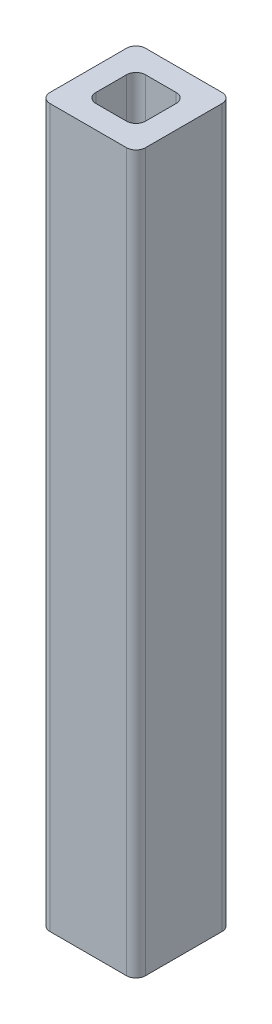
SolidWorks part; units mm, degrees
ref_plane "正面" through (0, 0, 0) normal (0, 0, 1) x (1, 0, 0)
ref_plane "平面" through (0, 0, 0) normal (0, 1, 0) x (1, 0, 0)
ref_plane "右側面" through (0, 0, 0) normal (1, 0, 0) x (0, 0, -1)
sketch "ｽｹｯﾁ1" plane through (0, 0, 0) normal (0, 1, 0) x (1, 0, 0)
  line L1 (-4, -5) -> (4, -5)
  line L2 (-5, -4) -> (-5, 4)
  line L3 (-4, 5) -> (4, 5)
  line L4 (5, -4) -> (5, 4)
  line L5 (-5, -5) -> (5, 5) construction
  line L6 (-5, 5) -> (5, -5) construction
  arc A1 (4, 5) -> (5, 4) centre (4, 4) cw
  arc A2 (-5, 4) -> (-4, 5) centre (-4, 4) cw
  arc A3 (-4, -5) -> (-5, -4) centre (-4, -4) cw
  arc A4 (4, -5) -> (5, -4) centre (4, -4) ccw
  point P0 (0, 0)
  dimension "D1" = 10
  dimension "D3" = 1
  dimension "D2" = 10
extrude "ﾎﾞｽ - 押し出し1" add sketch "ｽｹｯﾁ1" along normal blind 75
sketch "ｽｹｯﾁ2" plane through (0, 75, 0) normal (0, 1, 0) x (1, 0, 0)
  line L1 (-1.6, -2.6) -> (1.6, -2.6)
  line L2 (-2.6, -1.6) -> (-2.6, 1.6)
  line L3 (-1.6, 2.6) -> (1.6, 2.6)
  line L4 (2.6, -1.6) -> (2.6, 1.6)
  line L5 (-2.6, -2.6) -> (2.6, 2.6) construction
  line L6 (-2.6, 2.6) -> (2.6, -2.6) construction
  arc A0 (-1.6, -2.6) -> (-2.6, -1.6) centre (-1.6, -1.6) cw
  arc A1 (1.6, -2.6) -> (2.6, -1.6) centre (1.6, -1.6) ccw
  arc A2 (1.6, 2.6) -> (2.6, 1.6) centre (1.6, 1.6) cw
  arc A3 (-2.6, 1.6) -> (-1.6, 2.6) centre (-1.6, 1.6) cw
  point P0 (0, 0)
  dimension "D3" = 1
  dimension "D1" = 5.2
  dimension "D2" = 5.2
extrude "ｶｯﾄ - 押し出し1" cut sketch "ｽｹｯﾁ2" against normal blind 5
